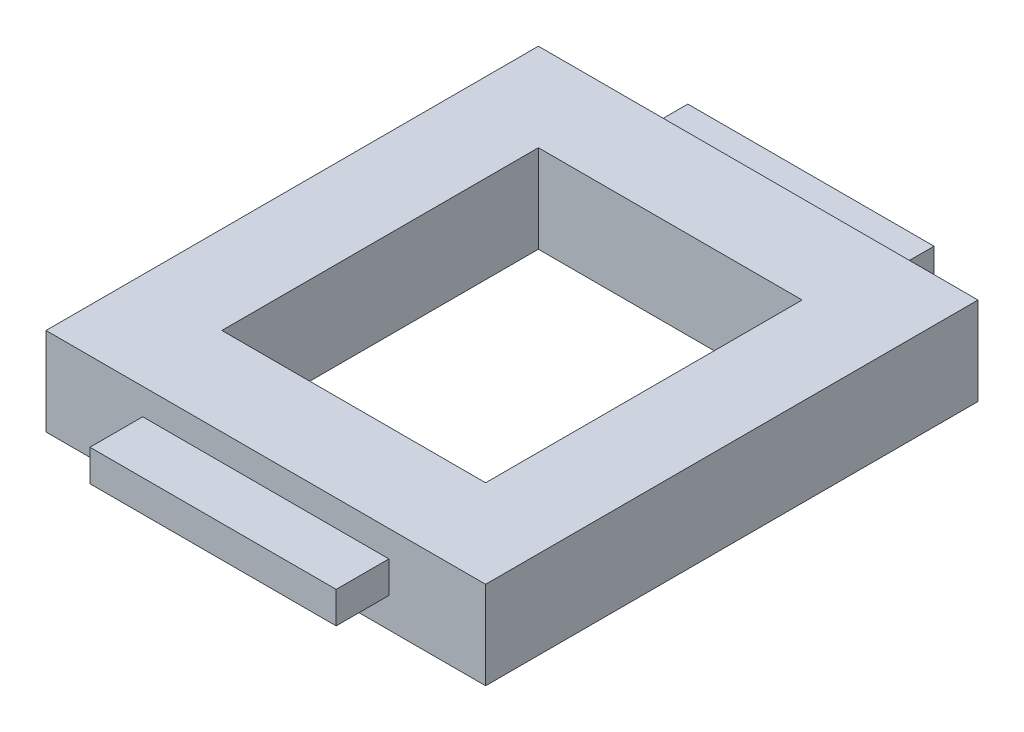
SolidWorks part; units mm, degrees
ref_plane "Front Plane" through (0, 0, 0) normal (0, 0, 1) x (1, 0, 0)
ref_plane "Top Plane" through (0, 0, 0) normal (0, 1, 0) x (1, 0, 0)
ref_plane "Right Plane" through (0, 0, 0) normal (1, 0, 0) x (0, 0, -1)
sketch "Sketch1" plane through (0, 0, 0) normal (0, 1, 0) x (1, 0, 0)
  line L1 (0, 0) -> (25, 0)
  line L2 (0, 0) -> (0, 28)
  line L3 (0, 28) -> (25, 28)
  line L4 (25, 0) -> (25, 28)
  line L5 (5, 23) -> (20, 23)
  line L6 (5, 23) -> (5, 5)
  line L7 (5, 5) -> (20, 5)
  line L8 (20, 23) -> (20, 5)
  dimension "D1" = 25
  dimension "D2" = 28
  dimension "D3" = 5
  dimension "D4" = 5
  dimension "D5" = 5
  dimension "D6" = 5
extrude "Boss-Extrude1" add sketch "Sketch1" along normal blind 5
sketch "Sketch2" plane through (0, 0, 0) normal (0, 0, 1) x (1, 0, 0)
  line L0 (0, 5) -> (0, 0) construction
  line L1 (5.5, 3.5) -> (19.5, 3.5)
  line L2 (5.5, 3.5) -> (5.5, 1.7)
  line L3 (5.5, 1.7) -> (19.5, 1.7)
  line L4 (19.5, 3.5) -> (19.5, 1.7)
  line L5 (25, 5) -> (25, 0) construction
  line L7 (0, 0) -> (25, 0) construction
  dimension "D1" = 5.5
  dimension "D2" = 5.5
  dimension "D3" = 1.8
  dimension "D4" = 1.7
extrude "Boss-Extrude2" add sketch "Sketch2" along normal blind 3
sketch "Sketch3" plane through (0, 0, -28) normal (0, 0, -1) x (-1, 0, 0)
  line L0 (-25, 5) -> (-25, 0) construction
  line L1 (-19.5, 3.4) -> (-5.5, 3.4)
  line L2 (-19.5, 3.4) -> (-19.5, 1.6)
  line L3 (-19.5, 1.6) -> (-5.5, 1.6)
  line L4 (-5.5, 3.4) -> (-5.5, 1.6)
  line L5 (0, 5) -> (0, 0) construction
  line L6 (-25, 0) -> (0, 0) construction
  dimension "D1" = 5.5
  dimension "D2" = 5.5
  dimension "D3" = 1.6
  dimension "D4" = 1.8
extrude "Boss-Extrude3" add sketch "Sketch3" along normal blind 3
